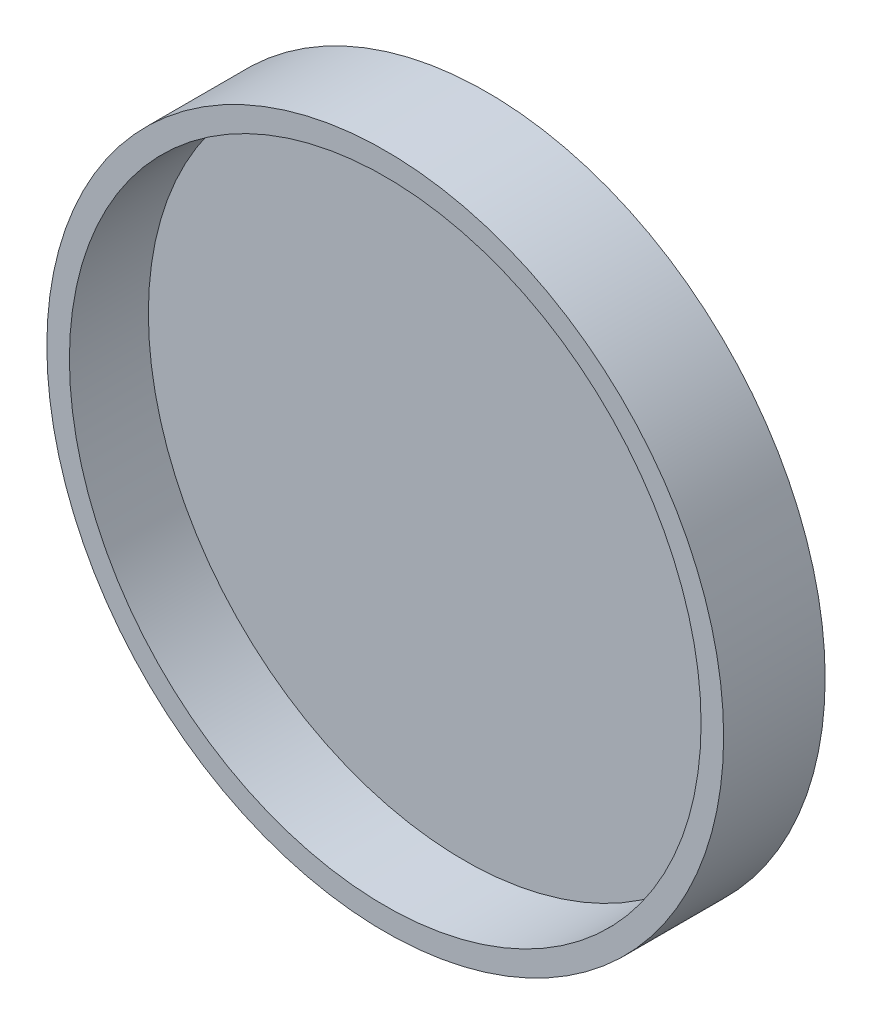
SolidWorks part; units mm, degrees
ref_plane "Front Plane" through (0, 0, 0) normal (0, 0, 1) x (1, 0, 0)
ref_plane "Top Plane" through (0, 0, 0) normal (0, 1, 0) x (1, 0, 0)
ref_plane "Right Plane" through (0, 0, 0) normal (1, 0, 0) x (0, 0, -1)
sketch "Sketch2" plane through (0, 0, 0) normal (0, 0, 1) x (1, 0, 0)
  circle A0 centre (0, 0) radius 15
  dimension "D1" = 30
extrude "Boss-Extrude1" add sketch "Sketch2" along normal blind 4.5
sketch "Sketch3" plane through (0, 0, 4.5) normal (0, 0, 1) x (1, 0, 0)
  circle A0 centre (0, 0) radius 14
  dimension "D1" = 28
extrude "Cut-Extrude1" cut sketch "Sketch3" against normal offset from surface (3.5 mm away) 1 up to face at (15, 0, 0)
